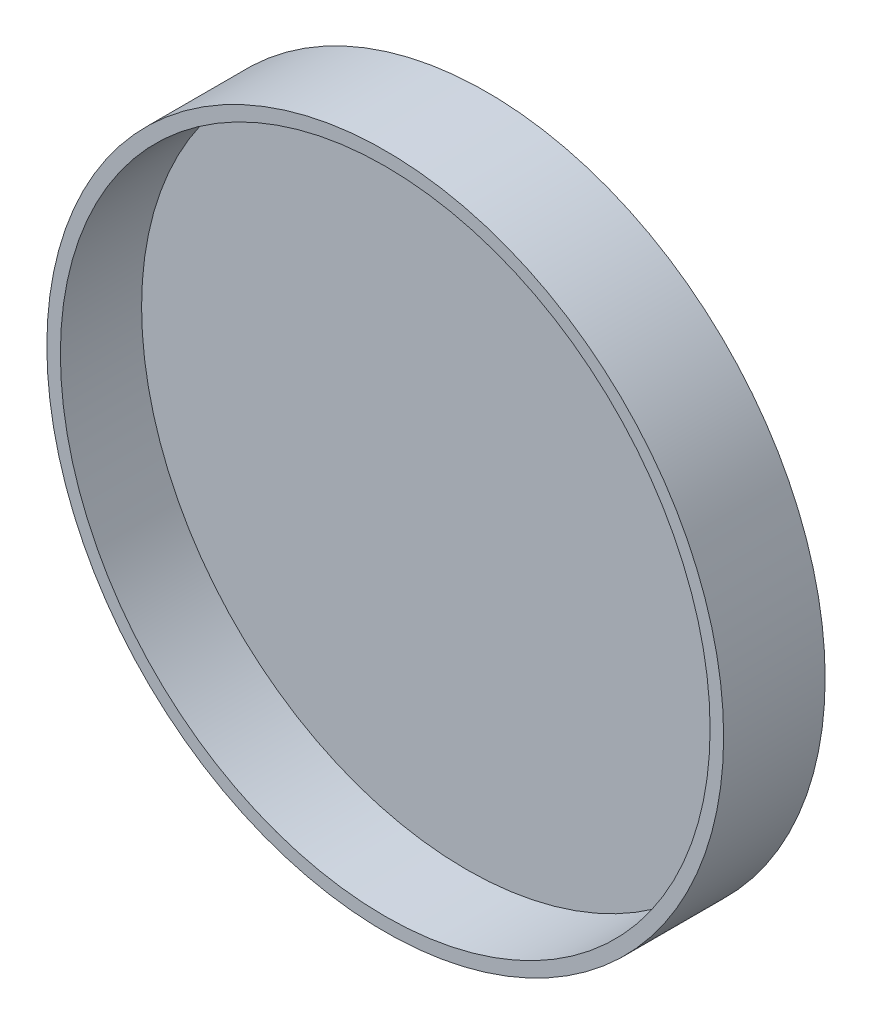
SolidWorks part; units mm, degrees
ref_plane "Front Plane" through (0, 0, 0) normal (0, 0, 1) x (1, 0, 0)
ref_plane "Top Plane" through (0, 0, 0) normal (0, 1, 0) x (1, 0, 0)
ref_plane "Right Plane" through (0, 0, 0) normal (1, 0, 0) x (0, 0, -1)
sketch "Sketch1" plane through (0, 0, 0) normal (0, 0, 1) x (1, 0, 0)
  circle A0 centre (0, 0) radius 50
  dimension "D1" = 100
extrude "Boss-Extrude1" add sketch "Sketch1" along normal blind 15
sketch "Sketch2" plane through (0, 0, 15) normal (0, 0, 1) x (1, 0, 0)
  circle A0 centre (0, 0) radius 48
  dimension "D1" = 96
extrude "Cut-Extrude1" cut sketch "Sketch2" against normal blind 12
